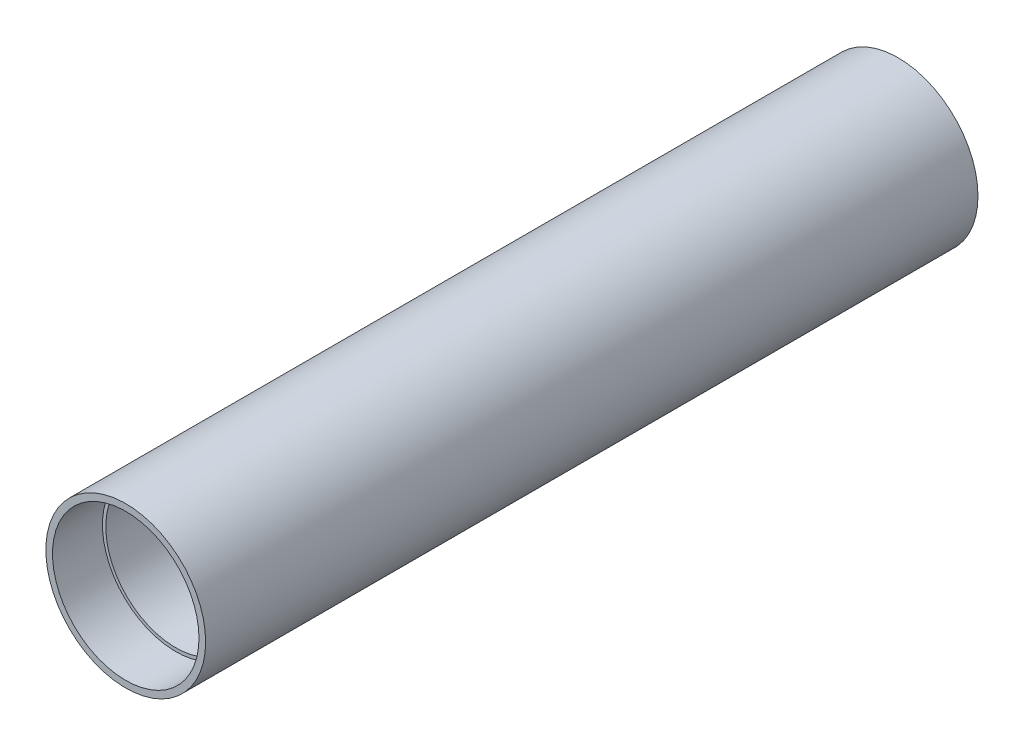
SolidWorks part; units mm, degrees
material "СТ3КП"
ref_plane "Спереди" through (0, 0, 0) normal (0, 0, 1) x (1, 0, 0)
ref_plane "Сверху" through (0, 0, 0) normal (0, 1, 0) x (1, 0, 0)
ref_plane "Справа" through (0, 0, 0) normal (1, 0, 0) x (0, 0, -1)
sketch "Эскиз1" plane through (0, 0, 0) normal (1, 0, 0) x (0, 0, -1)
  line L0 (-1000, 0) -> (49000, 0) construction
  line L1 (0, -1000) -> (0, 49000) construction
  line L3 (0, 24) -> (-116, 24)
  line L4 (0, 24) -> (0, 21)
  line L5 (0, 21) -> (-101, 21)
  line L6 (-116, 24) -> (-116, 22)
  line L7 (-116, 22) -> (-101, 22)
  line L10 (-101, 22) -> (-101, 21)
  dimension "D1" = 15
  dimension "D2" = 48
  dimension "D3" = 232
  dimension "D4" = 3
  dimension "D5" = 44
revolve "Повернуть1" add sketch "Эскиз1" angle 360 about L0
mirror "Зеркальное отражение1" about plane through (0, 24, 0) normal (0, 0, 1) of "Повернуть1"
